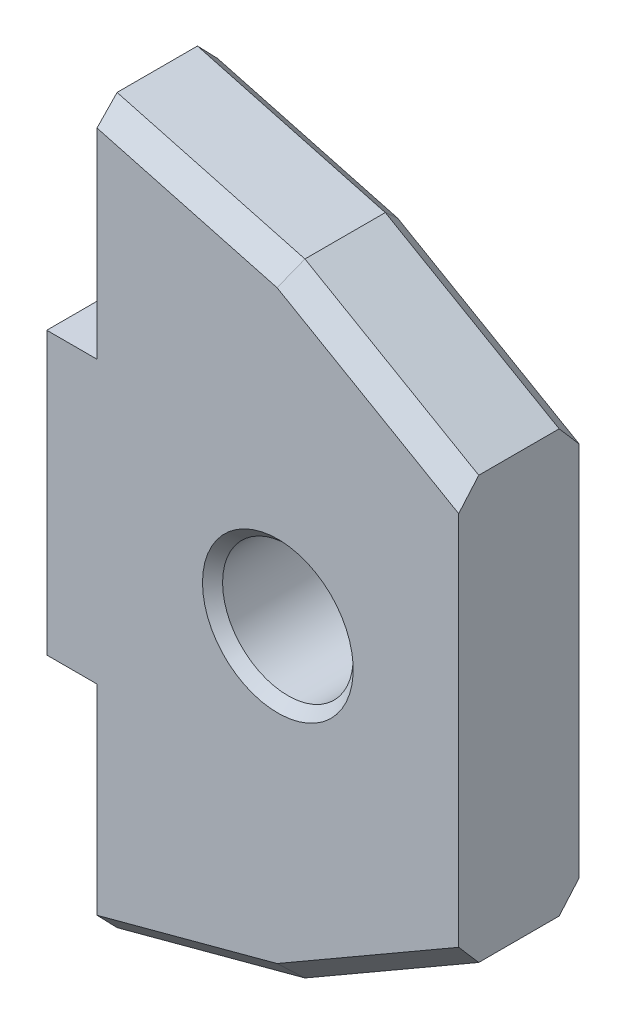
SolidWorks part; units mm, degrees
ref_plane "前视基准面" through (0, 0, 0) normal (0, 0, 1) x (1, 0, 0)
ref_plane "上视基准面" through (0, 0, 0) normal (0, 1, 0) x (1, 0, 0)
ref_plane "右视基准面" through (0, 0, 0) normal (1, 0, 0) x (0, 0, -1)
other "Configuration Table"
sketch "草图1" plane through (0, 0, 0) normal (0, 0, 1) x (1, 0, 0)
  line L0 (0, 0) -> (-15.5566, 0) construction
  line L1 (-23, -14) -> (-23, 14)
  line L2 (-23, 14) -> (-18, 14)
  line L3 (-18, 14) -> (-18, 36)
  line L4 (-18, 36) -> (0.6962, 30.9904)
  line L5 (0.6962, 30.9904) -> (18, 21)
  line L6 (18, 21) -> (18, -21)
  line L7 (0.6962, -30.9904) -> (18, -21)
  line L8 (-18, -36) -> (0.6962, -30.9904)
  line L9 (-18, -14) -> (-18, -36)
  line L10 (-23, -14) -> (-18, -14)
  circle A0 centre (0, 0) radius 6.5
  point P13 (18, 0)
  point P18 (-23, 0)
  dimension "D9" = 6.5
  dimension "D1" = 18
  dimension "D2" = 28
  dimension "D3" = 15
  dimension "D4" = 30
  dimension "D5" = 42
  dimension "D6" = 41
  dimension "D7" = 5
  dimension "D8" = 72
extrude "凸台-拉伸1" add sketch "草图1" along normal mid plane 12 contours L4 L5 L6 L7 L8 L9 L10 L1 L2 L3 | A0
chamfer "倒角1" distance 2 angle 45 8 edges at (9.3481, -25.9952, -6) (-8.6519, -33.4952, -6) (9.3481, -25.9952, 6) (-8.6519, -33.4952, 6) (-8.6519, 33.4952, -6) (9.3481, 25.9952, -6) (9.3481, 25.9952, 6) (-8.6519, 33.4952, 6)
chamfer "倒角2" distance 1 angle 45 2 edges at (-6.5, 0, -6) (-6.5, 0, 6)
